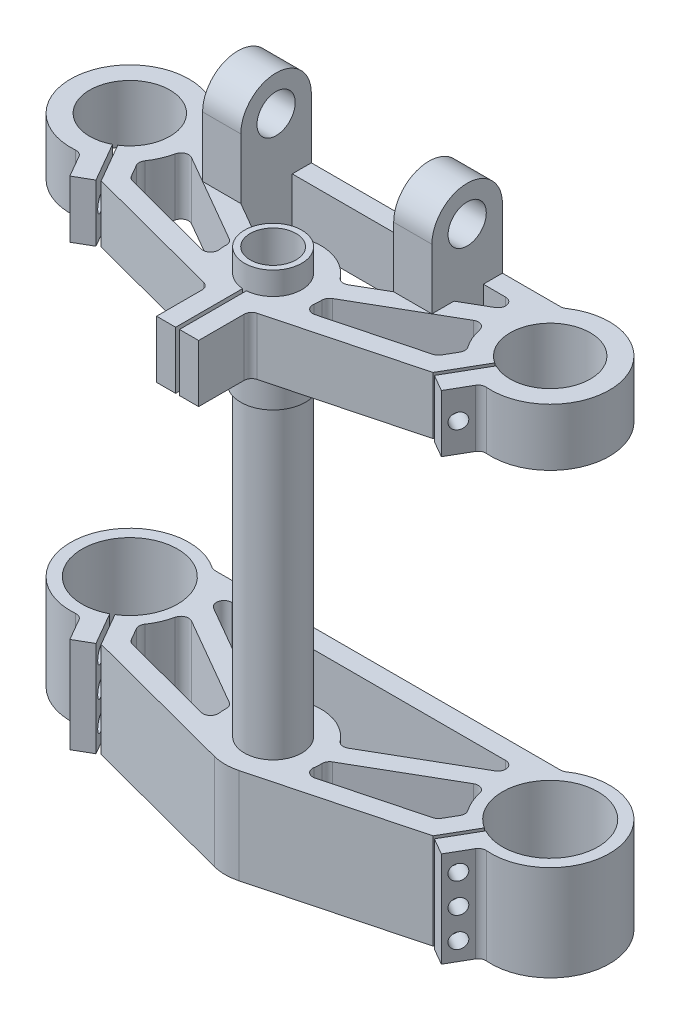
SolidWorks part; units mm, degrees
material "6061 Alloy"
ref_plane "Front Plane" through (0, 0, 0) normal (0, 0, 1) x (1, 0, 0)
ref_plane "Top Plane" through (0, 0, 0) normal (0, 1, 0) x (1, 0, 0)
ref_plane "Right Plane" through (0, 0, 0) normal (1, 0, 0) x (0, 0, -1)
sketch "Sketch1" plane through (0, 0, 0) normal (0, 1, 0) x (1, 0, 0)
  line L0 (-110, 35) -> (110, 35) construction
  line L1 (-13.9814, -22.341) -> (-86.812, -3.1628)
  line L2 (-90.4041, 60) -> (90.4041, 60)
  line L4 (-97.2043, -9.1628) -> (-103.7149, 2.1139)
  line L5 (-97.2043, -9.1628) -> (-88.5441, -4.1628)
  line L7 (-11, -26.2091) -> (-11, -50)
  line L8 (0, 0) -> (0, 48.5597) construction
  line L9 (11, -26.2091) -> (11, -50)
  line L10 (110, 35) -> (78.3659, -19.7919) construction
  line L11 (88.5441, -4.1628) -> (100.3779, 16.3341)
  line L12 (-11, -50) -> (-1, -50)
  line L13 (-1, -14.9666) -> (-1, -50)
  line L14 (1, -14.9666) -> (1, -50)
  line L15 (1, -50) -> (11, -50)
  line L16 (86.812, -3.1628) -> (13.9814, -22.341)
  line L17 (86.812, -3.1628) -> (98.6459, 17.3341)
  line L18 (-86.812, -3.1628) -> (-98.6459, 17.3341)
  line L19 (-88.5441, -4.1628) -> (-100.3779, 16.3341)
  line L20 (-110, 35) -> (-78.3659, -19.7919) construction
  line L21 (97.2043, -9.1628) -> (88.5441, -4.1628)
  line L22 (97.2043, -9.1628) -> (103.7149, 2.1139)
  line L23 (-71.6743, 50) -> (71.6743, 50)
  line L24 (-29.744, -7.8494) -> (-78.6235, 5.0218)
  line L25 (-81.069, 6.89) -> (-84.6623, 13.1139)
  line L26 (81.069, 6.89) -> (84.6623, 13.1139)
  line L27 (78.6235, 5.0218) -> (29.744, -7.8494)
  line L28 (-7.1803, -13.791) -> (-80.2355, 5.4463) construction
  line L29 (80.2355, 5.4463) -> (5.9491, -14.1152) construction
  line L30 (-24.8747, 14.3614) -> (-73.6743, 42.5359)
  line L31 (-26.9943, 4.0382) -> (-73.7927, 31.0572)
  line L32 (-5, -8.6603) -> (-82.4415, 36.0506) construction
  line L33 (0, 0) -> (-77.4415, 44.7109) construction
  line L34 (26.9943, 4.0382) -> (73.7927, 31.0572)
  line L35 (24.8747, 14.3614) -> (73.6743, 42.5359)
  line L36 (80.2355, 5.4463) -> (85.9823, 15.4002) construction
  line L37 (-80.2355, 5.4463) -> (-85.9823, 15.4002) construction
  line L38 (86.812, -3.1628) -> (8.4955, -23.7856) construction
  line L39 (-9.7268, -23.4614) -> (-86.812, -3.1628) construction
  arc A0 (1, -14.9666) -> (-1, -14.9666) centre (0, 0) ccw
  arc A1 (-98.6459, 17.3341) -> (-100.3779, 16.3341) centre (-110, 35) ccw
  arc A2 (100.3779, 16.3341) -> (98.6459, 17.3341) centre (110, 35) ccw
  circle A3 centre (-110, 35) radius 21 construction
  arc A4 (-92.6436, 60.6857) -> (-107.5014, 4.1009) centre (-110, 35) ccw
  arc A5 (107.5014, 4.1009) -> (92.6436, 60.6857) centre (110, 35) ccw
  circle A6 centre (110, 35) radius 21 construction
  circle A7 centre (-110, 35) radius 31 construction
  circle A8 centre (110, 35) radius 31 construction
  arc A9 (-84.4899, 17.3866) -> (-79.7021, 28.4396) centre (-110, 35) ccw
  arc A10 (24.7633, -3.4321) -> (24.9951, 0.4949) centre (0, 0) ccw
  arc A11 (79.7021, 28.4396) -> (84.4899, 17.3866) centre (110, 35) ccw
  arc A12 (-85.9823, 15.4002) -> (-95.796, 7.4456) centre (-110, 35) ccw construction
  arc A13 (95.796, 7.4456) -> (85.9823, 15.4002) centre (110, 35) ccw construction
  arc A14 (1.6667, -24.9444) -> (-1.6667, -24.9444) centre (0, 0) ccw construction
  arc A15 (-24.9951, 0.4949) -> (-24.7633, -3.4321) centre (0, 0) ccw
  arc A16 (19.7196, 15.3668) -> (-19.7196, 15.3668) centre (0, 0) ccw
  arc A17 (103.7149, 2.1139) -> (107.5014, 4.1009) centre (107.179, 0.1139) cw
  arc A18 (-107.5014, 4.1009) -> (-103.7149, 2.1139) centre (-107.179, 0.1139) cw
  arc A19 (92.6436, 60.6857) -> (90.4041, 60) centre (90.4041, 64) cw
  arc A20 (-92.6436, 60.6857) -> (-90.4041, 60) centre (-90.4041, 64) ccw
  arc A21 (81.069, 6.89) -> (78.6235, 5.0218) centre (77.6049, 8.89) cw
  arc A22 (84.4899, 17.3866) -> (84.6623, 13.1139) centre (81.1982, 15.1139) cw
  arc A23 (73.7927, 31.0572) -> (79.7021, 28.4396) centre (75.7927, 27.5931) cw
  arc A24 (-78.6235, 5.0218) -> (-81.069, 6.89) centre (-77.6049, 8.89) cw
  arc A25 (-84.6623, 13.1139) -> (-84.4899, 17.3866) centre (-81.1982, 15.1139) cw
  arc A26 (-73.7927, 31.0572) -> (-79.7021, 28.4396) centre (-75.7927, 27.5931) ccw
  arc A27 (-26.9943, 4.0382) -> (-24.9951, 0.4949) centre (-28.9943, 0.5741) cw
  arc A28 (-24.7633, -3.4321) -> (-29.744, -7.8494) centre (-28.7254, -3.9813) cw
  arc A29 (24.7633, -3.4321) -> (29.744, -7.8494) centre (28.7254, -3.9813) ccw
  arc A30 (26.9943, 4.0382) -> (24.9951, 0.4949) centre (28.9943, 0.5741) ccw
  arc A31 (24.8747, 14.3614) -> (19.7196, 15.3668) centre (22.8747, 17.8255) cw
  arc A32 (-24.8747, 14.3614) -> (-19.7196, 15.3668) centre (-22.8747, 17.8255) ccw
  arc A33 (71.6743, 50) -> (73.6743, 42.5359) centre (71.6743, 46) cw
  arc A34 (-73.6743, 42.5359) -> (-71.6743, 50) centre (-71.6743, 46) cw
  arc A35 (11, -26.2091) -> (13.9814, -22.341) centre (15, -26.2091) cw
  arc A36 (-11, -26.2091) -> (-13.9814, -22.341) centre (-15, -26.2091) ccw
  point P7 (0, 35)
  point P40 (0, 50)
  point P66 (98.3591, -0.1221)
  point P69 (-98.3591, -0.1221)
  point P82 (79.0139, 34.0717)
  point P91 (-79.0139, 34.0717)
  point P94 (-24.8431, 2.7962)
  point P101 (24.8431, 2.7962)
  point P104 (21.6506, 12.5)
  point P107 (-21.6506, 12.5)
  point P110 (86.6025, 50)
  point P117 (11, -23.1261)
  point P121 (-11, -23.1261)
  dimension "D1" = 30
  dimension "D4" = 42
  dimension "D18" = 4
  dimension "D19" = 4
  dimension "D20" = 4
  dimension "D2" = 35
  dimension "D3" = 220
  dimension "D6" = 25
  dimension "D7" = 2
  dimension "D8" = 2
  dimension "D9" = 10
  dimension "D10" = 50
  dimension "D11" = 14.753
  dimension "D12" = 60
  dimension "D13" = 10
  dimension "D14" = 10
  dimension "D17" = 60
  dimension "D5" = 10
  dimension "D15" = 10
  dimension "D16" = 10
extrude "Boss-Extrude1" add sketch "Sketch1" along normal mid plane 260
sketch "Sketch3" plane through (0, 0, 0) normal (0, 0, 1) x (1, 0, 0)
  line L1 (-141, -80) -> (141, -80)
  line L2 (-141, -80) -> (-141, 100)
  line L3 (-141, 100) -> (141, 100)
  line L4 (141, -80) -> (141, 100)
  line L5 (141, -130) -> (141, 130) construction
  line L6 (-141, 130) -> (-141, -130) construction
  line L7 (-86.812, -130) -> (-13.9814, -130) construction
  point P0 (0, 0)
  dimension "D1" = 180
  dimension "D2" = 50
extrude "Cut-Extrude2" cut sketch "Sketch3" against normal through all and the other way through all
sketch "Sketch4" plane through (-76.8708, 0, 44.3814) normal (-0.866, 0, 0.5) x (0.5, 0, 0.866)
  line L0 (-53.6881, 130) -> (-40.667, 130) construction
  line L1 (-40.667, -80) -> (-53.6881, -80) construction
  line L3 (-53.6881, -130) -> (-40.667, -130) construction
  circle A0 centre (-47.1775, 115) radius 4
  circle A1 centre (-47.1775, -89.5) radius 4
  circle A2 centre (-47.1775, -105) radius 4
  circle A3 centre (-47.1775, -120.5) radius 4
  point P4 (-47.1775, 130)
  point P9 (-47.1775, -80)
  dimension "D1" = 8
  dimension "D3" = 8
  dimension "D2" = 15
  dimension "D4" = 9.5
  dimension "D6" = 9.5
  dimension "D5" = 3
extrude "Cut-Extrude3" cut sketch "Sketch4" against normal up to surface (52.2872 mm away)
sketch "Sketch5" plane through (0, -130, 0) normal (0, -1, 0) x (1, 0, 0)
  line L0 (-1, 14.9666) -> (-1, 25.145)
  line L1 (-1, 50) -> (-1, 14.9666) construction
  line L2 (1, 14.9666) -> (1, 25.145)
  line L3 (1, 14.9666) -> (1, 50) construction
  line L4 (-86.812, 3.1628) -> (-13.9814, 22.341) construction
  arc A0 (1, 14.9666) -> (-1, 14.9666) centre (0, 0) ccw
  arc A1 (1, 25.145) -> (-1, 25.145) centre (0, 0) ccw
extrude "Boss-Extrude2" add sketch "Sketch5" against normal up to surface (50 mm away) up to face at (58.8176, -80, -9.5144)
sketch "Sketch6" plane through (0, -130, 0) normal (0, -1, 0) x (1, 0, 0)
  line L0 (-86.812, 3.1628) -> (-13.9814, 22.341) construction
  line L1 (-13.9814, 22.341) -> (-6.4081, 24.3353)
  line L2 (-13.9814, 22.341) -> (-13.9814, 50)
  line L3 (-13.9814, 50) -> (13.9814, 50)
  line L4 (0, 0) -> (0, 13.2143) construction
  line L5 (13.9814, 22.341) -> (13.9814, 50)
  line L6 (13.9814, 22.341) -> (6.4081, 24.3353)
  line L7 (-11, 50) -> (-1, 50) construction
  arc A0 (6.4081, 24.3353) -> (-6.4081, 24.3353) centre (0, 0) ccw
  circle A1 centre (110, -35) radius 25
  circle A2 centre (-110, -35) radius 25
  dimension "D1" = 50
extrude "Cut-Extrude4" cut sketch "Sketch6" against normal up to surface (50 mm away) up to face at (0, -80, -1.2926)
sketch "Sketch7" plane through (-11, 0, 0) normal (-1, 0, 0) x (0, 0, 1)
  line L0 (26.2091, 130) -> (50, 130) construction
  line L1 (50, 130) -> (50, 100) construction
  circle A0 centre (38.1046, 115) radius 4
  point P4 (38.1046, 130)
  point P7 (50, 115)
  dimension "D1" = 8
extrude "Cut-Extrude5" cut sketch "Sketch7" against normal up to next (10 mm away)
mirror "Mirror1" about plane through (0, 0, 0) normal (1, 0, 0) of "Cut-Extrude3"
sketch "Sketch8" plane through (0, 0, 0) normal (0, 0, 1) x (1, 0, 0)
  line L0 (-15, -130) -> (-15, 80)
  line L2 (0, 0) -> (0, 50.5937) construction
  line L3 (-15, 142) -> (-12, 142)
  line L4 (-12, 142) -> (-12, -130)
  line L5 (-86.812, -130) -> (-6.4081, -130) construction
  line L6 (-12, -130) -> (-15, -130)
  line L7 (-15, 100) -> (-17, 100)
  line L8 (-86.812, 100) -> (-13.9814, 100) construction
  line L9 (-17, 100) -> (-17, 80)
  line L10 (-17, 80) -> (-15, 80)
  line L11 (-15, 100) -> (-15, 142)
  line L12 (-86.812, 130) -> (-13.9814, 130) construction
  dimension "D1" = 2
  dimension "D2" = 20
  dimension "D3" = 12
  dimension "D4" = 3
revolve "Revolve1" add sketch "Sketch8" angle 360 about L2
sketch "Sketch9" plane through (0, 100, 0) normal (0, -1, 0) x (1, 0, 0)
  line L0 (90.4041, -60) -> (-90.4041, -60) construction
  line L1 (-60, -60) -> (-40, -60)
  line L2 (-60, -60) -> (-60, -23.094)
  line L3 (-60, -23.094) -> (-40, -23.094)
  line L4 (-40, -60) -> (-40, -23.094)
  line L5 (-73.6743, -42.5359) -> (-24.8747, -14.3614) construction
  line L6 (0, 0) -> (0, -72.8786) construction
  line L7 (-26.9943, -4.0382) -> (-73.7927, -31.0572) construction
  line L8 (40, -60) -> (40, -23.094)
  line L9 (60, -23.094) -> (40, -23.094)
  line L10 (60, -60) -> (60, -23.094)
  line L11 (60, -60) -> (40, -60)
  dimension "D1" = 40
extrude "Boss-Extrude3" add sketch "Sketch9" against normal offset from surface (80 mm away) 50 up to face at (-58.8176, 130, -9.5144) offset beyond the face yes
sketch "Sketch10" plane through (0, 0, 0) normal (1, 0, 0) x (0, 0, -1)
  line L0 (23.094, 180) -> (60, 180) construction
  line L1 (60, 180) -> (60, 130) construction
  line L2 (60, 161.547) -> (60, 180)
  line L3 (60, 180) -> (23.094, 180)
  line L4 (23.094, 180) -> (23.094, 161.547)
  circle A0 centre (41.547, 161.547) radius 10
  arc A1 (60, 161.547) -> (23.094, 161.547) centre (41.547, 161.547) ccw
  point P4 (41.547, 180)
  dimension "D1" = 20
extrude "Cut-Extrude6" cut sketch "Sketch10" against normal through all and the other way through all contours A1 L2 L3 | A1 L3 L4 | A0
